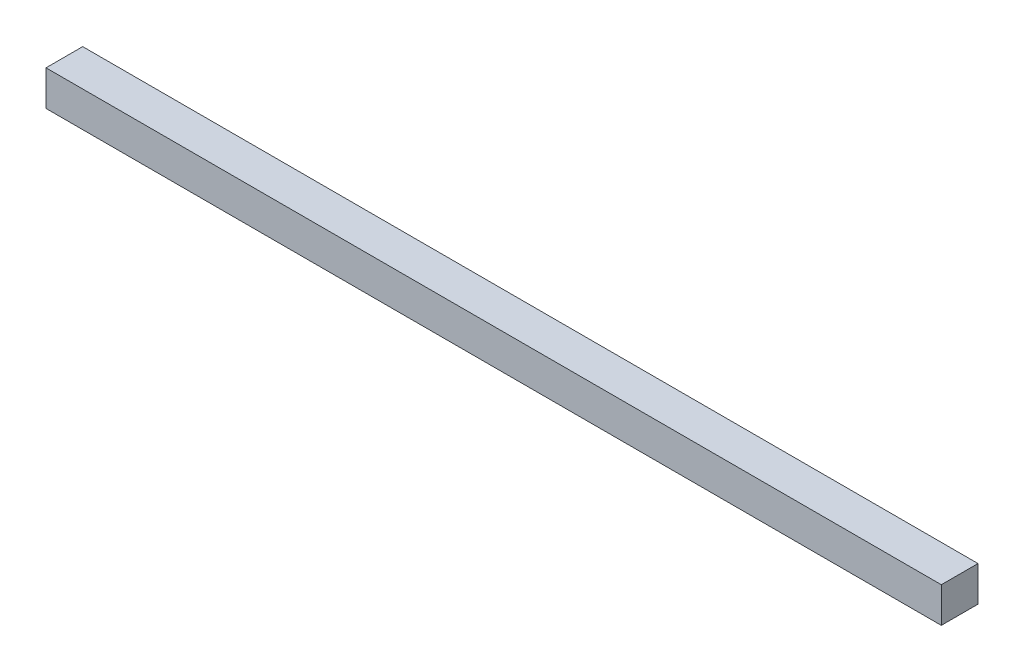
SolidWorks part; units mm, degrees
ref_plane "Front Plane" through (0, 0, 0) normal (0, 0, 1) x (1, 0, 0)
ref_plane "Top Plane" through (0, 0, 0) normal (0, 1, 0) x (1, 0, 0)
ref_plane "Right Plane" through (0, 0, 0) normal (1, 0, 0) x (0, 0, -1)
sketch "Sketch1" plane through (0, 0, 0) normal (0, 1, 0) x (1, 0, 0)
  line L1 (-152.5, -125) -> (152.5, -125)
  line L2 (-152.5, -125) -> (-152.5, 125)
  line L3 (-152.5, 125) -> (152.5, 125)
  line L4 (152.5, -125) -> (152.5, 125)
  line L5 (-152.5, -125) -> (152.5, 125) construction
  line L6 (-152.5, 125) -> (152.5, -125) construction
  line L7 (-165, -137.5) -> (165, -137.5)
  line L8 (-165, -137.5) -> (-165, 137.5)
  line L9 (-165, 137.5) -> (165, 137.5)
  line L10 (165, -137.5) -> (165, 137.5)
  line L11 (-165, -137.5) -> (165, 137.5) construction
  line L12 (-165, 137.5) -> (165, -137.5) construction
  point P0 (0, 0)
  point P5 (0, 0)
extrude "Boss-Extrude4" add sketch "Sketch1" along normal blind 12
sketch "Sketch2" plane through (165, 0, 0) normal (1, 0, 0) x (0, 0, -1)
  line L0 (0, 12) -> (0, 152) construction
  line L1 (-137.5, 12) -> (137.5, 12) construction
  line L2 (0, 152) -> (-137.5, 12)
  line L3 (-137.5, 12) -> (-127.5, 12)
  line L4 (-127.5, 12) -> (0, 141.8182)
  line L5 (0, 152) -> (137.5, 12)
  line L6 (137.5, 12) -> (127.5, 12)
  line L7 (0, 141.8182) -> (127.5, 12)
extrude "Boss-Extrude6" add sketch "Sketch2" against normal up to surface (12.5 mm away) up to face at (152.5, 6, 0)
sketch "Sketch5" plane through (-165, 0, 0) normal (-1, 0, 0) x (0, 0, 1)
  line L0 (0, 12) -> (0, 152) construction
  line L1 (-137.5, 12) -> (137.5, 12) construction
  line L2 (0, 152) -> (-137.5, 12)
  line L3 (-137.5, 12) -> (-127.5, 12)
  line L4 (-127.5, 12) -> (0, 141.8182)
  line L5 (0, 152) -> (137.5, 12)
  line L6 (137.5, 12) -> (127.5, 12)
  line L7 (127.5, 12) -> (0, 141.8182)
extrude "Boss-Extrude7" add sketch "Sketch5" against normal up to surface (12.5 mm away) up to face at (-152.5, 6, 0)
sketch "Sketch6" plane through (152.5, 0, 0) normal (-1, 0, 0) x (0, 0, 1)
  line L0 (0, 152) -> (0, 141.8182) construction
  circle A0 centre (0, 146.9091) radius 11
  circle A1 centre (0, 146.9091) radius 15
extrude "Boss-Extrude8" add sketch "Sketch6" against normal up to surface (12.5 mm away) up to face at (165, 55.2727, 0)
sketch "Sketch7" plane through (152.5, 0, 0) normal (-1, 0, 0) x (0, 0, 1)
  line L0 (0, 152) -> (0, 141.8182) construction
  circle A0 centre (0, 146.9091) radius 11
extrude "Cut-Extrude2" cut sketch "Sketch7" against normal through all
sketch "Sketch8" plane through (0, 69.6316, 70.8976) normal (0, -0.7007, -0.7134) x (-1, 0, 0)
  line L0 (152.5, 101.1799) -> (152.5, -80.7789) construction
  line L1 (152.5, -80.7789) -> (-152.5, -80.7789) construction
  line L2 (-152.5, -80.7789) -> (0, -80.7789) construction
  line L3 (0, -80.7789) -> (0, 71.6699) construction
  line L4 (165, 101.1799) -> (165, -80.7789) construction
  line L5 (140, 15.2005) -> (165, 15.2005)
  line L6 (140, 15.2005) -> (140, 5.2005)
  line L7 (140, 5.2005) -> (165, 5.2005)
  line L8 (165, 15.2005) -> (165, 5.2005)
  line L9 (140, 15.2005) -> (165, 5.2005) construction
  line L10 (140, 5.2005) -> (165, 15.2005) construction
  line L11 (152.5, 15.2005) -> (152.5, 5.2005)
  line L12 (-140, 5.2005) -> (-165, 5.2005)
  line L13 (-165, 15.2005) -> (-165, 5.2005)
  line L14 (-140, 15.2005) -> (-165, 15.2005)
  line L15 (-140, 15.2005) -> (-140, 5.2005)
  line L16 (-152.5, 15.2005) -> (-152.5, 5.2005)
  point P4 (152.5, 10.2005)
  line M7 (152.5, 101.1799) -> (152.5, -80.7789)
  line M9 (165, -80.7789) -> (165, 101.1799)
extrude "Boss-Extrude9" add sketch "Sketch8" along normal up to surface (87.5427 mm away) contours L16 L14 L13 L12 | L7 L5 M7 M9
sketch "Sketch9" plane through (0, 69.6316, -70.8976) normal (0, -0.7007, 0.7134) x (1, 0, 0)
  line L0 (-152.5, 101.1799) -> (-152.5, -80.7789) construction
  line L1 (-152.5, -80.7789) -> (152.5, -80.7789) construction
  line L2 (152.5, -80.7789) -> (0, -80.7789) construction
  line L3 (0, -80.7789) -> (0, 71.5896) construction
  line L4 (-165, -80.7789) -> (-165, 101.1799) construction
  line L5 (-140, 5.2005) -> (-165, 5.2005)
  line L6 (-140, 5.2005) -> (-140, 15.2005)
  line L7 (-140, 15.2005) -> (-165, 15.2005)
  line L8 (-165, 5.2005) -> (-165, 15.2005)
  line L9 (-140, 5.2005) -> (-165, 15.2005) construction
  line L10 (-140, 15.2005) -> (-165, 5.2005) construction
  line L11 (-152.5, 5.2005) -> (-152.5, 15.2005)
  line L12 (140, 15.2005) -> (165, 15.2005)
  line L13 (165, 5.2005) -> (165, 15.2005)
  line L14 (140, 5.2005) -> (165, 5.2005)
  line L15 (140, 5.2005) -> (140, 15.2005)
  line L16 (152.5, 5.2005) -> (152.5, 15.2005)
  point P9 (-152.5, 10.2005)
  line M7 (-152.5, -80.7789) -> (-152.5, 101.1799)
  line M9 (-165, 101.1799) -> (-165, -80.7789)
extrude "Boss-Extrude10" add sketch "Sketch9" along normal up to surface (87.5427 mm away) contours L7 L5 M7 M9 | L16 L14 L13 L12
sketch "Sketch10" plane through (-152.5, 0, 0) normal (1, 0, 0) x (0, 0, -1)
  line L0 (0, 152) -> (0, 141.8182) construction
  line L2 (-12.5, 134.4091) -> (12.5, 134.4091)
  line L3 (-12.5, 134.4091) -> (-12.5, 159.4091)
  line L4 (-12.5, 159.4091) -> (12.5, 159.4091)
  line L5 (12.5, 134.4091) -> (12.5, 159.4091)
  line L6 (-12.5, 134.4091) -> (12.5, 159.4091) construction
  line L7 (-12.5, 159.4091) -> (12.5, 134.4091) construction
  point P4 (0, 146.9091)
extrude "Boss-Extrude11" add sketch "Sketch10" against normal up to surface (12.5 mm away) up to face at (-165, 27.9098, 52.841)
sketch "Sketch11" plane through (0, 0, 0) normal (0, 0, 1) x (1, 0, 0)
  line L0 (152.5, 157.9091) -> (152.5, 135.9091) construction
  line L1 (152.5, 161.9091) -> (146.5169, 161.9091)
  line L2 (152.5, 161.9091) -> (152.5, 157.9091)
  line L3 (152.5, 157.9091) -> (146.5169, 157.9091)
  line L4 (146.5169, 161.9091) -> (146.5169, 157.9091)
  line L5 (152.5, 146.9091) -> (128.8664, 146.9091) construction
  circle A0 centre (149.5084, 163.7989) radius 3.5385
revolve "Revolve1" add sketch "Sketch11" angle 360 about L5
sketch "Sketch13" plane through (-165, 0, 0) normal (-1, 0, 0) x (0, 0, 1)
  line L1 (-137.5, 0) -> (161.0044, 0)
  line L2 (-137.5, 0) -> (-137.5, 174.0295)
  line L3 (-137.5, 174.0295) -> (161.0044, 174.0295)
  line L4 (161.0044, 0) -> (161.0044, 174.0295)
extrude "Cut-Extrude4" cut sketch "Sketch13" against normal blind 12.5
sketch "Sketch14" plane through (165, 0, 0) normal (1, 0, 0) x (0, 0, -1)
  line L0 (-12.7541, 139.014) -> (-137.5, 12) construction
  line L1 (-67.522, 83.2503) -> (114.8739, 83.2503)
  line L2 (-67.522, 83.2503) -> (-67.522, 176.5622)
  line L3 (-67.522, 176.5622) -> (114.8739, 176.5622)
  line L4 (114.8739, 83.2503) -> (114.8739, 176.5622)
extrude "Cut-Extrude5" cut sketch "Sketch14" against normal blind 71.5
sketch "Sketch15" plane through (165, 0, 0) normal (1, 0, 0) x (0, 0, -1)
  line L1 (-137.5, 0) -> (197.7957, 0)
  line L2 (-137.5, 0) -> (-137.5, 100.1187)
  line L3 (-137.5, 100.1187) -> (197.7957, 100.1187)
  line L4 (197.7957, 0) -> (197.7957, 100.1187)
extrude "Cut-Extrude6" cut sketch "Sketch15" against normal blind 12.5
sketch "Sketch16" plane through (152.5, 0, 0) normal (1, 0, 0) x (0, 0, -1)
  line L1 (125, 0) -> (194.3969, 0)
  line L2 (125, 0) -> (125, 36.2948)
  line L3 (125, 36.2948) -> (194.3969, 36.2948)
  line L4 (194.3969, 0) -> (194.3969, 36.2948)
extrude "Cut-Extrude7" cut sketch "Sketch16" against normal blind 362.5
